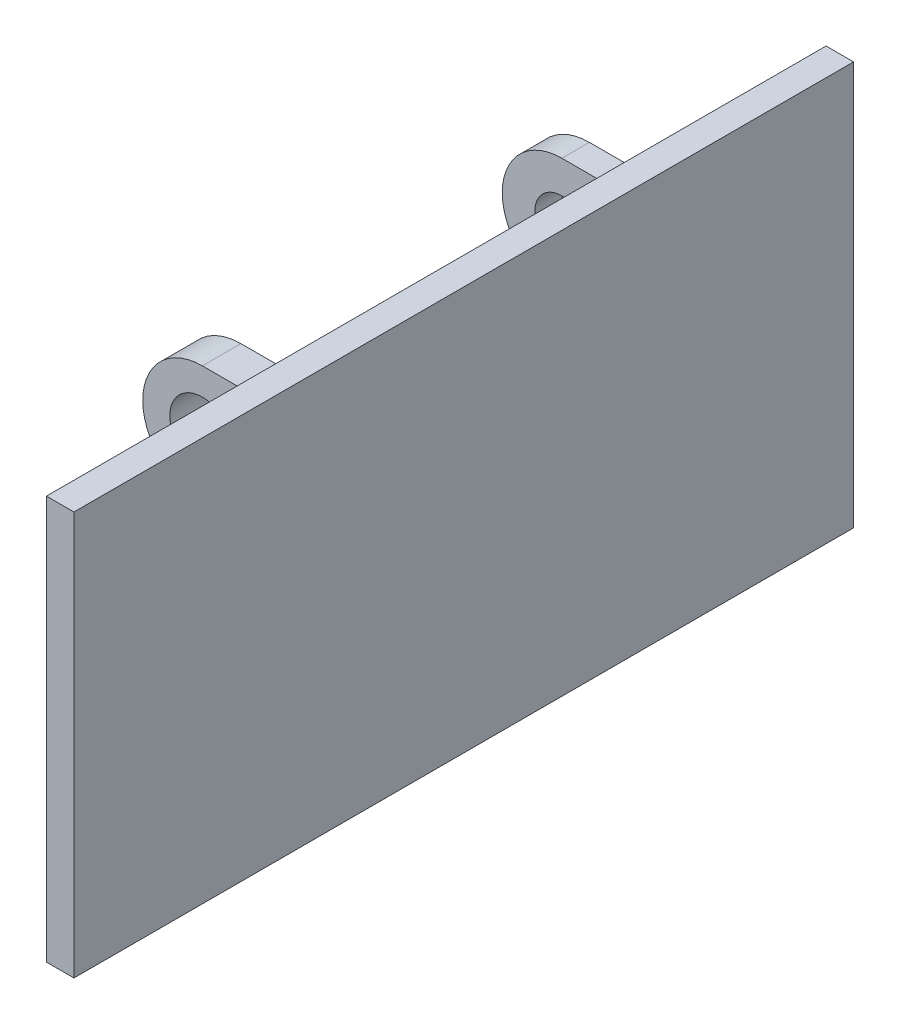
SolidWorks part; units mm, degrees
material "ABS"
ref_plane "Front Plane" through (0, 0, 0) normal (0, 0, 1) x (1, 0, 0)
ref_plane "Top Plane" through (0, 0, 0) normal (0, 1, 0) x (1, 0, 0)
ref_plane "Right Plane" through (0, 0, 0) normal (1, 0, 0) x (0, 0, -1)
sketch "Sketch1" plane through (0, 0, 0) normal (1, 0, 0) x (0, 0, -1)
  line L1 (-47, -46) -> (38, -46)
  line L2 (-47, -46) -> (-47, -2)
  line L3 (-47, -2) -> (38, -2)
  line L4 (38, -46) -> (38, -2)
extrude "Boss-Extrude1" add sketch "Sketch1" along normal mid plane 3 from offset 123.5
sketch "Sketch2" plane through (0, 0, 0) normal (0, 0, 1) x (1, 0, 0)
  circle A0 centre (108.2, -18.5) radius 6.5
extrude "Boss-Extrude2" add sketch "Sketch2" along normal mid plane 4.2 from offset 14.1
sketch "Sketch3" plane through (0, 0, 0) normal (0, 0, 1) x (1, 0, 0)
  line L1 (108.2, -25) -> (122.5, -25)
  line L2 (108.2, -25) -> (108.2, -12)
  line L3 (108.2, -12) -> (122.5, -12)
  line L4 (122.5, -25) -> (122.5, -12)
  circle A0 centre (108.2, -18.5) radius 6.5 construction
extrude "Boss-Extrude3" add sketch "Sketch3" along normal mid plane 4.2 from offset 14.1
sketch "Sketch4" plane through (0, 0, 0) normal (0, 0, 1) x (1, 0, 0)
  circle A0 centre (108.2, -18.5) radius 3.55
extrude "Cut-Extrude1" cut sketch "Sketch4" against normal mid plane 4.2 from offset 14.1
sketch "Sketch5" plane through (0, 0, 0) normal (0, 0, 1) x (1, 0, 0)
  line L0 (108.2, -14.95) -> (120.9, -16.0967)
  line L1 (120.9, -16.0967) -> (120.9, -20.9033)
  line L2 (120.9, -20.9033) -> (108.2, -22.05)
  line L3 (108.2, -22.05) -> (108.2, -14.95)
  circle A0 centre (108.2, -18.5) radius 3.55 construction
extrude "Cut-Extrude2" cut sketch "Sketch5" against normal mid plane 4.2 from offset 14.1
sketch "Sketch6" plane through (0, 0, 0) normal (0, 0, 1) x (1, 0, 0)
  circle A0 centre (108.2, -18.5) radius 6.5
extrude "Boss-Extrude4" add sketch "Sketch6" along normal mid plane 3 from offset 24.5
sketch "Sketch7" plane through (0, 0, 0) normal (0, 0, 1) x (1, 0, 0)
  line L1 (108.2, -25) -> (122.5, -25)
  line L2 (108.2, -25) -> (108.2, -12)
  line L3 (108.2, -12) -> (122.5, -12)
  line L4 (122.5, -25) -> (122.5, -12)
extrude "Boss-Extrude5" add sketch "Sketch7" along normal mid plane 3 from offset 24.5
sketch "Sketch8" plane through (0, 0, 0) normal (0, 0, 1) x (1, 0, 0)
  circle A0 centre (108.2, -18.5) radius 2.95
extrude "Cut-Extrude3" cut sketch "Sketch8" against normal mid plane 3 from offset 24.5
